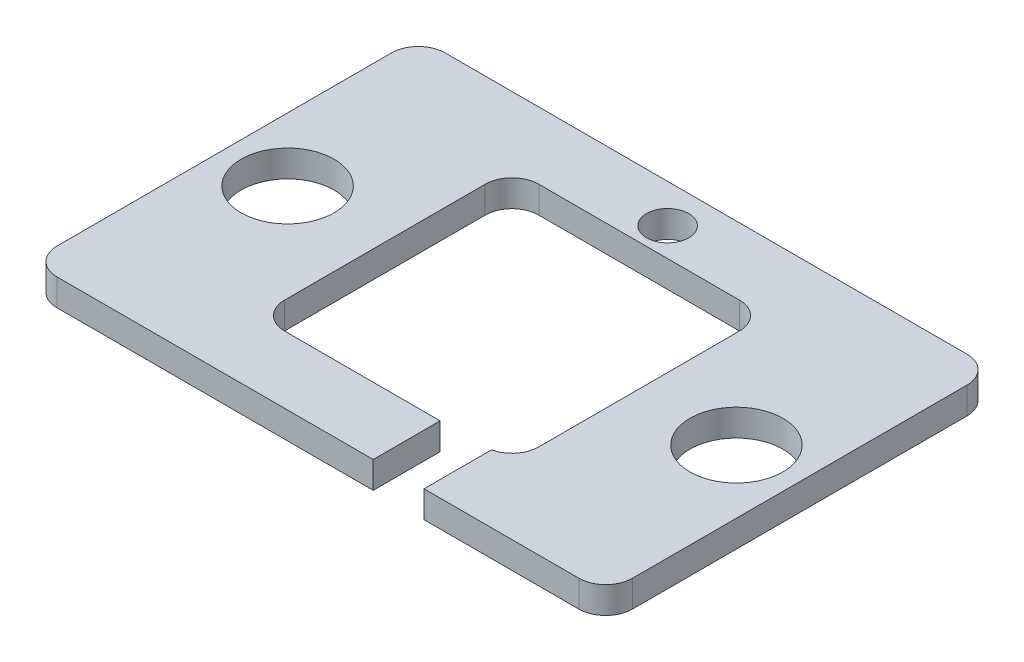
SolidWorks part; units mm, degrees
ref_plane "Front Plane" through (0, 0, 0) normal (0, 0, 1) x (1, 0, 0)
ref_plane "Top Plane" through (0, 0, 0) normal (0, 1, 0) x (1, 0, 0)
ref_plane "Right Plane" through (0, 0, 0) normal (1, 0, 0) x (0, 0, -1)
sketch "Sketch1" plane through (0, 0, 0) normal (0, 1, 0) x (1, 0, 0)
  line L0 (-16.77, 0) -> (16.77, 0) construction
  line L1 (-7.5, -9.5) -> (7.5, -9.5)
  line L2 (-9.5, -7.5) -> (-9.5, 7.5)
  line L3 (-7.5, 9.5) -> (7.5, 9.5)
  line L4 (9.5, -7.5) -> (9.5, 7.5)
  line L5 (-9.5, -9.5) -> (9.5, 9.5) construction
  line L6 (-9.5, 9.5) -> (9.5, -9.5) construction
  line L7 (-19.5, -14.5) -> (19.5, -14.5)
  line L8 (-21.5, -12.5) -> (-21.5, 12.5)
  line L9 (-19.5, 14.5) -> (19.5, 14.5)
  line L10 (21.5, -12.5) -> (21.5, 12.5)
  line L11 (-21.5, -14.5) -> (21.5, 14.5) construction
  line L12 (-21.5, 14.5) -> (21.5, -14.5) construction
  arc A0 (-9.5, -7.5) -> (-7.5, -9.5) centre (-7.5, -7.5) ccw
  arc A1 (7.5, -9.5) -> (9.5, -7.5) centre (7.5, -7.5) ccw
  arc A2 (21.5, -12.5) -> (19.5, -14.5) centre (19.5, -12.5) cw
  arc A3 (-19.5, -14.5) -> (-21.5, -12.5) centre (-19.5, -12.5) cw
  arc A4 (-21.5, 12.5) -> (-19.5, 14.5) centre (-19.5, 12.5) cw
  arc A5 (21.5, 12.5) -> (19.5, 14.5) centre (19.5, 12.5) ccw
  arc A6 (9.5, 7.5) -> (7.5, 9.5) centre (7.5, 7.5) ccw
  arc A7 (-9.5, 7.5) -> (-7.5, 9.5) centre (-7.5, 7.5) cw
  circle A8 centre (-16.77, 0) radius 3.475
  circle A9 centre (16.77, 0) radius 3.475
  point P0 (0, 0)
  point P6 (0, 0)
  point P47 (0, 0)
  point P48 (0, 0)
  point P53 (0, 0)
  dimension "D1" = 2
  dimension "D7" = 6.95
  dimension "D8" = 6.95
  dimension "D2" = 19
  dimension "D3" = 12
  dimension "D4" = 5
  dimension "D5" = 19
  dimension "D6" = 33.54
extrude "Boss-Extrude1" add sketch "Sketch1" along normal blind 2
sketch "Sketch2" plane through (0, 2, 0) normal (0, 1, 0) x (1, 0, 0)
  circle A0 centre (0, 11.63) radius 1.575
extrude "Cut-Extrude1" cut sketch "Sketch2" against normal through all
sketch "Sketch3" plane through (0, 2, 0) normal (0, 1, 0) x (1, 0, 0)
  line L1 (4.1284, -8.9943) -> (7.925, -8.9943)
  line L2 (4.1284, -8.9943) -> (4.1284, -14.5)
  line L3 (4.1284, -14.5) -> (7.925, -14.5)
  line L4 (7.925, -8.9943) -> (7.925, -14.5)
  line L5 (4.1284, -7.975) -> (4.1284, -10.175) construction
  line L6 (-19.5, -14.5) -> (19.5, -14.5) construction
  line L7 (7.925, -10.175) -> (7.925, -7.975) construction
  point P4 (0, 0)
extrude "Cut-Extrude2" cut sketch "Sketch3" against normal through all
equation "\"D5@Sketch1\"=\"D2@Sketch1\""
equation "\"D8@Sketch1\"=\"D7@Sketch1\""
